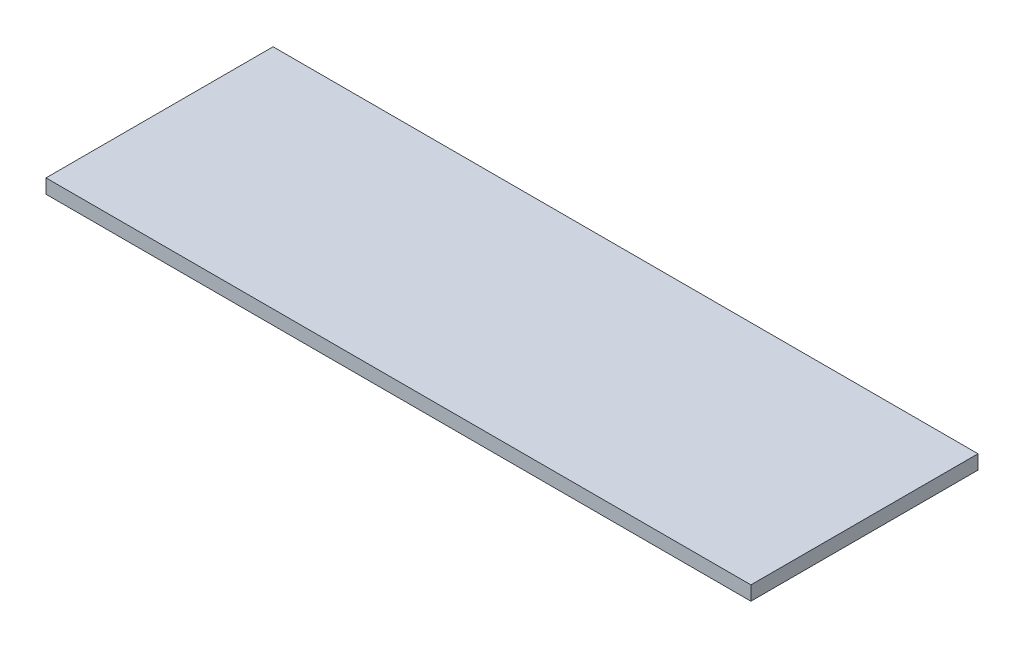
SolidWorks part; units mm, degrees
ref_plane "Front Plane" through (0, 0, 0) normal (0, 0, 1) x (1, 0, 0)
ref_plane "Top Plane" through (0, 0, 0) normal (0, 1, 0) x (1, 0, 0)
ref_plane "Right Plane" through (0, 0, 0) normal (1, 0, 0) x (0, 0, -1)
sketch "Sketch1" plane through (0, 0, 0) normal (0, 1, 0) x (1, 0, 0)
  line L1 (74.5, -24) -> (-74.5, -24)
  line L2 (74.5, -24) -> (74.5, 24)
  line L3 (74.5, 24) -> (-74.5, 24)
  line L4 (-74.5, -24) -> (-74.5, 24)
  line L5 (74.5, -24) -> (-74.5, 24) construction
  line L6 (74.5, 24) -> (-74.5, -24) construction
  point P0 (0, 0)
  dimension "D1" = 149
  dimension "D2" = 48
extrude "Boss-Extrude1" add sketch "Sketch1" along normal blind 3
